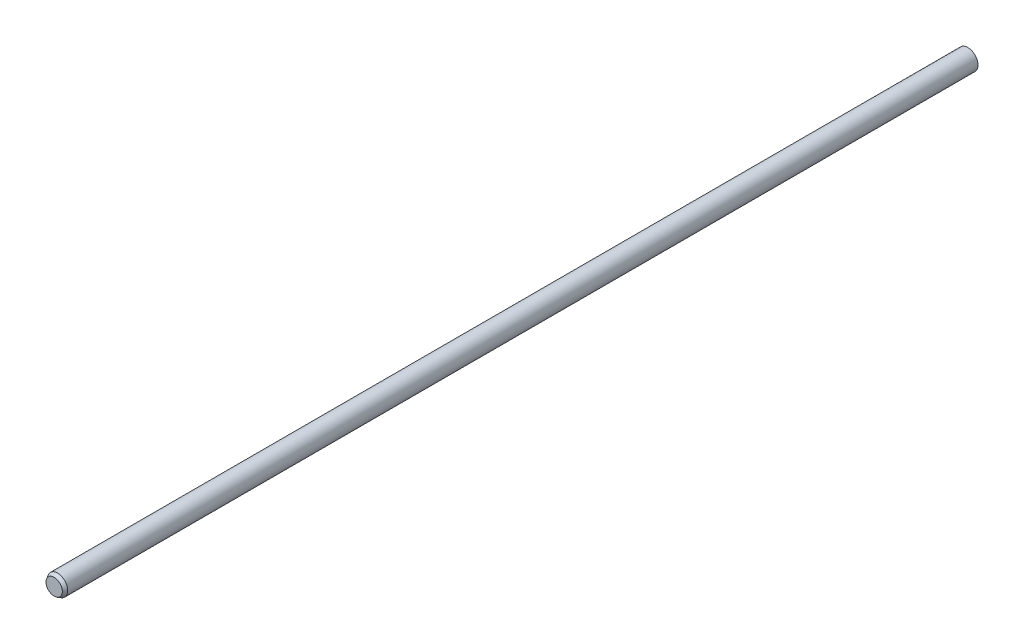
SolidWorks part; units mm, degrees
material "1060 Alloy"
ref_plane "Front Plane" through (0, 0, 0) normal (0, 0, 1) x (1, 0, 0)
ref_plane "Top Plane" through (0, 0, 0) normal (0, 1, 0) x (1, 0, 0)
ref_plane "Right Plane" through (0, 0, 0) normal (1, 0, 0) x (0, 0, -1)
sketch "Sketch1" plane through (0, 0, 0) normal (0, 0, 1) x (1, 0, 0)
  circle A0 centre (0, 0) radius 3
extrude "Boss-Extrude1" add sketch "Sketch1" along normal blind 271
chamfer "Chamfer1" distance 1 angle 30 2 edges at (3, 0, 271) (3, 0, 0)
